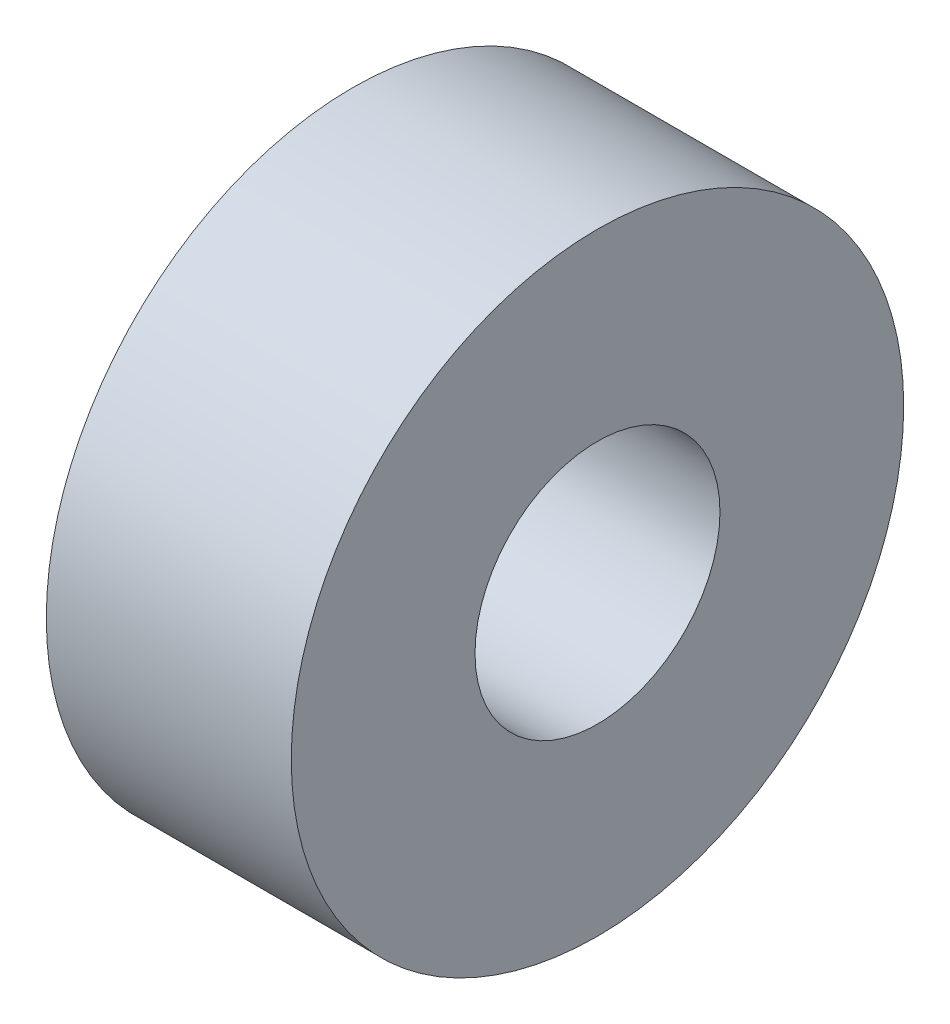
SolidWorks part; units mm, degrees
ref_plane "Front Plane" through (0, 0, 0) normal (0, 0, 1) x (1, 0, 0)
ref_plane "Top Plane" through (0, 0, 0) normal (0, 1, 0) x (1, 0, 0)
ref_plane "Right Plane" through (0, 0, 0) normal (1, 0, 0) x (0, 0, -1)
sketch "Sketch1" plane through (0, 0, 0) normal (0, 0, 1) x (1, 0, 0)
  line L0 (0, 0) -> (16, 0) construction
  line L1 (8, 15) -> (8, -15) construction
  line L2 (3, 12.5) -> (13, 12.5)
  line L3 (3, 12.5) -> (3, 5)
  line L4 (3, 5) -> (13, 5)
  line L5 (13, 12.5) -> (13, 5)
  line L6 (3, 15) -> (13, 15) construction
  point P7 (8, 0)
  dimension "W" = 16
  dimension "D1_s" = 10
  dimension "D" = 30
  dimension "B" = 10
  dimension "T" = 2.5
revolve "Revolve1" add sketch "Sketch1" angle 360 about L0
